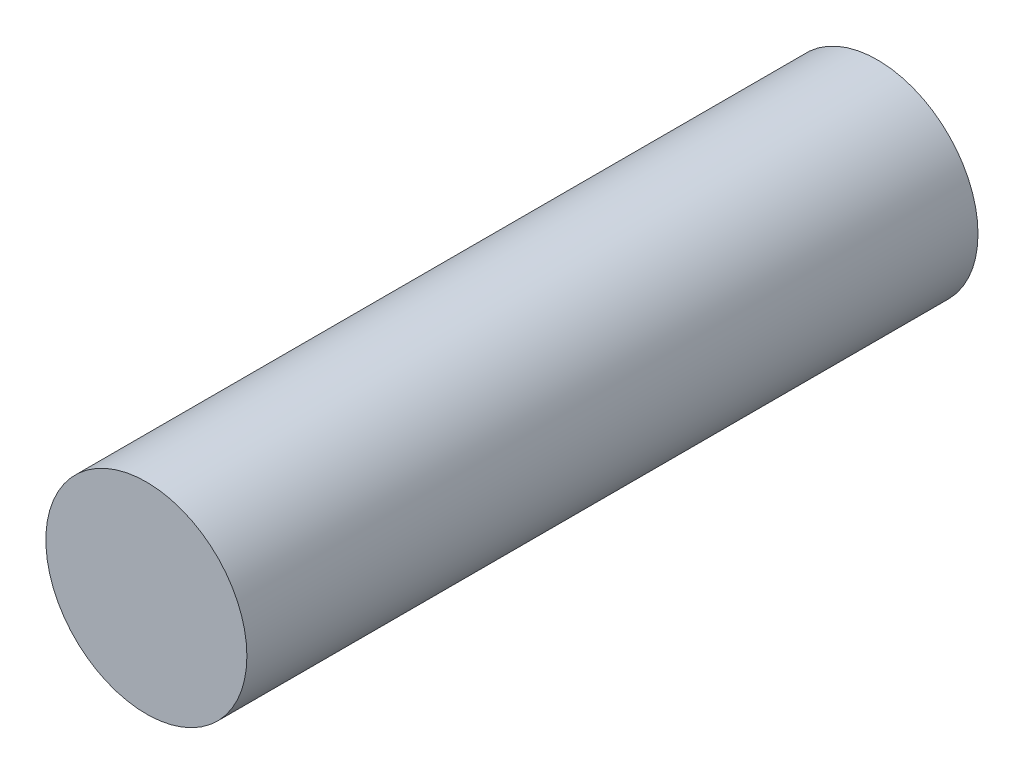
SolidWorks part; units mm, degrees
ref_plane "Front Plane" through (0, 0, 0) normal (0, 0, 1) x (1, 0, 0)
ref_plane "Top Plane" through (0, 0, 0) normal (0, 1, 0) x (1, 0, 0)
ref_plane "Right Plane" through (0, 0, 0) normal (1, 0, 0) x (0, 0, -1)
sketch "Sketch1" plane through (0, 0, 0) normal (0, 0, 1) x (1, 0, 0)
  circle A0 centre (0, 0) radius 5.5
  dimension "D1" = 11
extrude "Boss-Extrude1" add sketch "Sketch1" along normal blind 40
